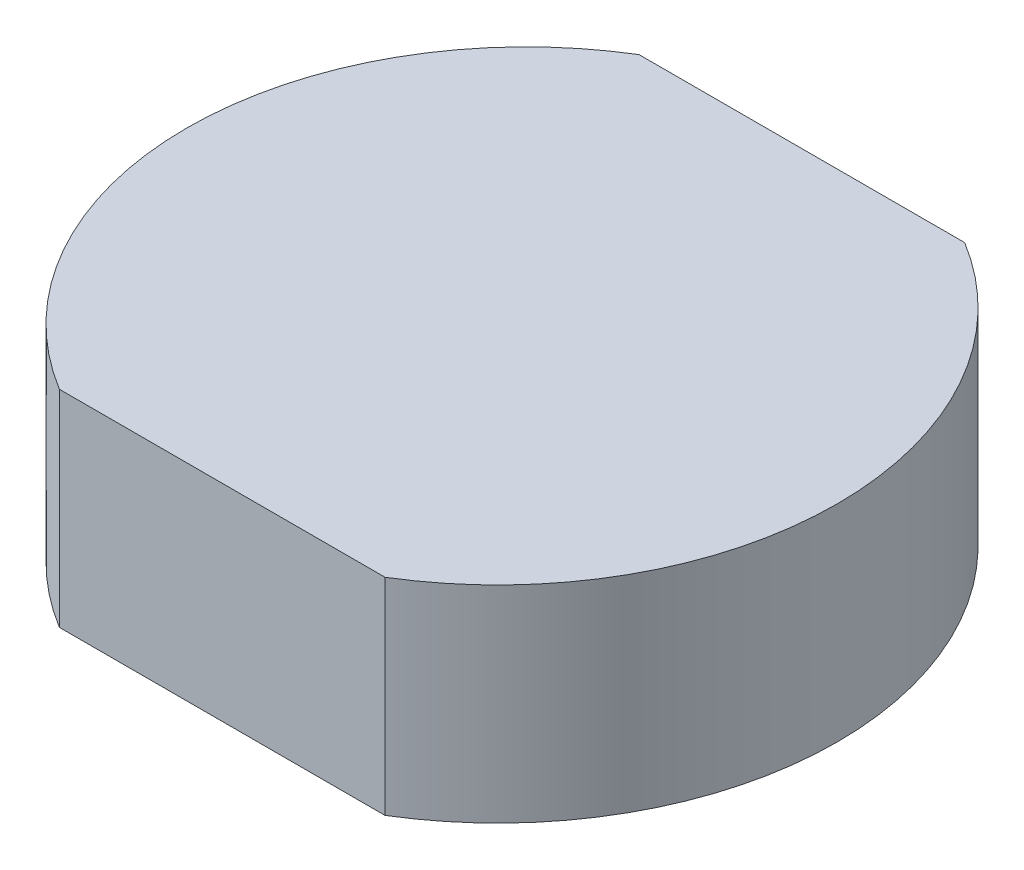
SolidWorks part; units mm, degrees
ref_plane "Front Plane" through (0, 0, 0) normal (0, 0, 1) x (1, 0, 0)
ref_plane "Top Plane" through (0, 0, 0) normal (0, 1, 0) x (1, 0, 0)
ref_plane "Right Plane" through (0, 0, 0) normal (1, 0, 0) x (0, 0, -1)
sketch "Sketch1" plane through (0, 0, 0) normal (0, 1, 0) x (1, 0, 0)
  line L0 (-16.7603, 0) -> (22.2815, 0) construction
  line L1 (4.2583, 7.05) -> (-4.2583, 7.05) construction
  line L2 (0, 7.05) -> (0, 0) construction
  line L3 (-8.05, 0) -> (8.05, 0)
  line L4 (4.2583, -7.05) -> (-4.2583, -7.05) construction
  line L5 (4.3476, -7.35) -> (-4.3476, -7.35)
  line L6 (4.3476, 7.35) -> (-4.3476, 7.35)
  line L7 (4.578, -8.15) -> (-4.578, -8.15)
  line L8 (4.578, 8.15) -> (-4.578, 8.15)
  arc A1 (-4.2583, 7.05) -> (-4.2583, -7.05) centre (0.4, 0) ccw construction
  arc A2 (4.2583, 7.05) -> (4.2583, -7.05) centre (-0.4, 0) cw construction
  arc A3 (-4.3476, 7.35) -> (-4.3476, -7.35) centre (0.4, 0) ccw
  arc A4 (4.3476, 7.35) -> (4.3476, -7.35) centre (-0.4, 0) cw
  arc A5 (-4.578, 8.15) -> (-4.578, -8.15) centre (0.4, 0) ccw
  arc A6 (4.578, 8.15) -> (4.578, -8.15) centre (-0.4, 0) cw
  dimension "D1" = 16.1
  dimension "D4" = 16.9
  dimension "D2" = 0.3
  dimension "D3" = 7.05
  dimension "D5" = 0.4
  dimension "D6" = 0.8
extrude "Boss-Extrude1" add sketch "Sketch1" along normal blind 5 contours A6 L8 A5 L7 L6 A4 L5 A3
sketch "Sketch2" plane through (0, 5, 0) normal (0, 1, 0) x (1, 0, 0)
  line L0 (4.578, -8.15) -> (-4.578, -8.15) construction
  line L1 (4.578, 8.15) -> (-4.578, 8.15) construction
  line L2 (4.578, -8.15) -> (-4.578, -8.15)
  line L3 (4.578, 8.15) -> (-4.578, 8.15)
  arc A0 (4.578, -8.15) -> (4.578, 8.15) centre (-0.4, 0) ccw construction
  arc A1 (-4.578, 8.15) -> (-4.578, -8.15) centre (0.4, 0) ccw construction
  arc A2 (4.578, -8.15) -> (4.578, 8.15) centre (-0.4, 0) ccw
  arc A3 (-4.578, 8.15) -> (-4.578, -8.15) centre (0.4, 0) ccw
extrude "Boss-Extrude2" add sketch "Sketch2" along normal blind 0.8
sketch "Sketch3" plane through (0, 0, 0) normal (1, 0, 0) x (0, 0, -1)
  line L0 (-8.15, 0) -> (8.15, 0) construction
  line L1 (-2, 2) -> (-2, 0)
  line L2 (2, 2) -> (2, 0)
  line L3 (-2, 0) -> (2, 0)
  arc A0 (2, 2) -> (-2, 2) centre (0, 2) ccw
  dimension "D1" = 4
extrude "Cut-Extrude1" cut sketch "Sketch3" against normal through all
